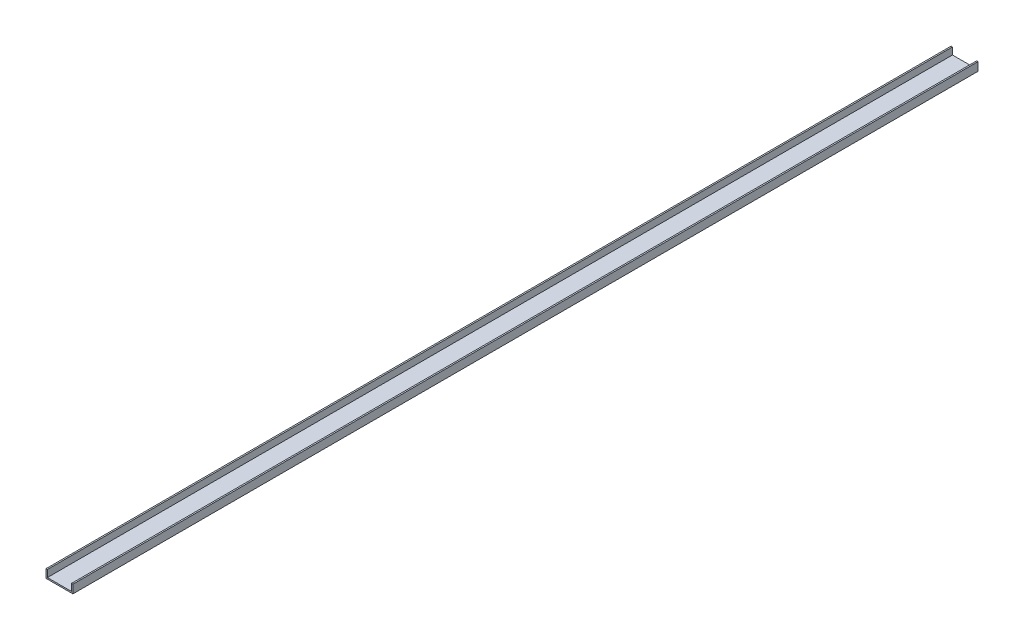
SolidWorks part; units mm, degrees
ref_plane "Front" through (0, 0, 0) normal (0, 0, 1) x (1, 0, 0)
ref_plane "Top" through (0, 0, 0) normal (0, 1, 0) x (1, 0, 0)
ref_plane "Right" through (0, 0, 0) normal (1, 0, 0) x (0, 0, -1)
sketch "Sketch1" plane through (0, 0, 0) normal (0, 0, 1) x (1, 0, 0)
  line L0 (-68.2625, 0) -> (68.2625, 0)
  line L1 (-76.2, -7.9375) -> (76.2, -7.9375)
  line L2 (0, -7.9375) -> (0, 0) construction
  line L3 (-76.2, -7.9375) -> (-76.2, 39.6875)
  line L4 (-76.2, 39.6875) -> (-68.2625, 39.6875)
  line L5 (-68.2625, 39.6875) -> (-68.2625, 0)
  line L6 (76.2, -7.9375) -> (76.2, 39.6875)
  line L7 (76.2, 39.6875) -> (68.2625, 39.6875)
  line L8 (68.2625, 39.6875) -> (68.2625, 0)
  dimension "Width" = 152.4
  dimension "Height" = 47.625
  dimension "Wall Thickness" = 7.9375
sketch "Sketch2" plane through (0, 0, 0) normal (1, 0, 0) x (0, 0, -1)
  line L0 (914.4, 0) -> (-914.4, 0) construction
  dimension "Length" = 1828.8
sketch "Sketch3" plane through (0, 0, 0) normal (0, 0, 1) x (1, 0, 0)
  line L0 (-68.2625, 39.6875) -> (-68.2625, 0) construction
  line L1 (-68.2625, 0) -> (68.2625, 0) construction
  line L2 (68.2625, 39.6875) -> (68.2625, 0) construction
  line L3 (76.2, 39.6875) -> (68.2625, 39.6875) construction
  line L4 (76.2, -7.9375) -> (76.2, 39.6875) construction
  line L5 (-76.2, -7.9375) -> (76.2, -7.9375) construction
  line L6 (-76.2, -7.9375) -> (-76.2, 39.6875) construction
  line L7 (-76.2, 39.6875) -> (-68.2625, 39.6875) construction
  line L8 (-68.2625, 39.6875) -> (-68.2625, 0)
  line L9 (-68.2625, 0) -> (68.2625, 0)
  line L10 (68.2625, 39.6875) -> (68.2625, 0)
  line L11 (76.2, 39.6875) -> (68.2625, 39.6875)
  line L12 (76.2, -7.9375) -> (76.2, 39.6875)
  line L13 (-76.2, -7.9375) -> (76.2, -7.9375)
  line L14 (-76.2, -7.9375) -> (-76.2, 39.6875)
  line L15 (-76.2, 39.6875) -> (-68.2625, 39.6875)
extrude "Boss-Extrude1" add sketch "Sketch3" along normal blind 5124.45
sketch "Sketch4" plane through (0, 0, 0) normal (0, 0, 1) x (1, 0, 0)
  line L0 (76.2, 39.6875) -> (76.2, 0) construction
  line L1 (68.2625, 0) -> (-68.2625, 0) construction
  line L2 (76.2, -7.9375) -> (68.2625, -7.9375) construction
  line L3 (-76.2, -7.9375) -> (76.2, -7.9375) construction
  line L4 (68.2625, 39.6875) -> (68.2625, 0) construction
